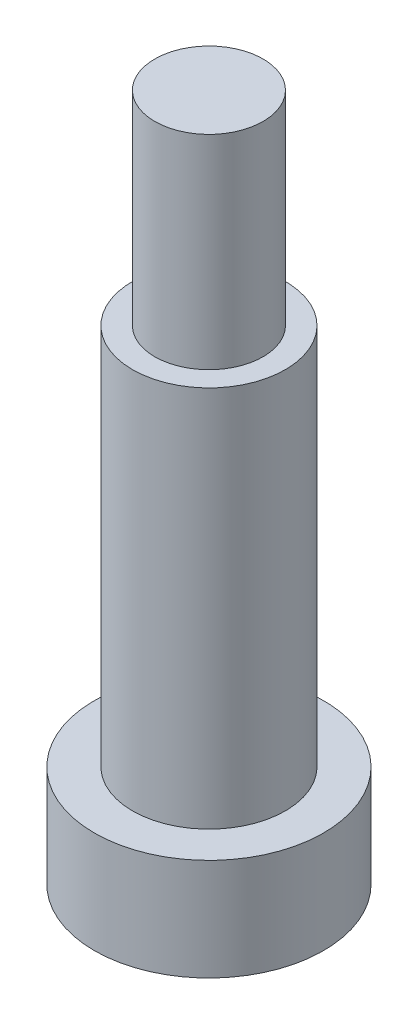
SolidWorks part; units mm, degrees
material "Acero aleado"
ref_plane "Alzado" through (0, 0, 0) normal (0, 0, 1) x (1, 0, 0)
ref_plane "Planta" through (0, 0, 0) normal (0, 1, 0) x (1, 0, 0)
ref_plane "Vista lateral" through (0, 0, 0) normal (1, 0, 0) x (0, 0, -1)
sketch "Croquis1" plane through (0, 0, 0) normal (0, 1, 0) x (1, 0, 0)
  circle A0 centre (0, -171.45) radius 4.25
  dimension "D1" = 8.5
  dimension "D2" = 171.45
extrude "Rosca_M10" add sketch "Croquis1" along normal blind 16 from offset 10.35
sketch "Croquis2" plane through (0, 0, 0) normal (0, 1, 0) x (1, 0, 0)
  circle A0 centre (0, -171.45) radius 6
  dimension "D1" = 12
  dimension "D2" = 171.45
extrude "Hombro_D12" add sketch "Croquis2" along normal blind 30 from offset 40.35
sketch "Croquis3" plane through (0, 0, 0) normal (0, 1, 0) x (1, 0, 0)
  circle A0 centre (0, -171.45) radius 9
  dimension "D1" = 18
  dimension "D2" = 171.45
extrude "Cabeza" add sketch "Croquis3" along normal blind 8 from offset 48.35
sketch "Croquis4" plane through (0, 0, 0) normal (0, 1, 0) x (1, 0, 0)
  circle A0 centre (0, -171.45) radius 3.96
  dimension "D1" = 7.92
  dimension "D2" = 171.45
extrude "Allen" cut sketch "Croquis4" along normal blind 4.8 from offset 48.35
